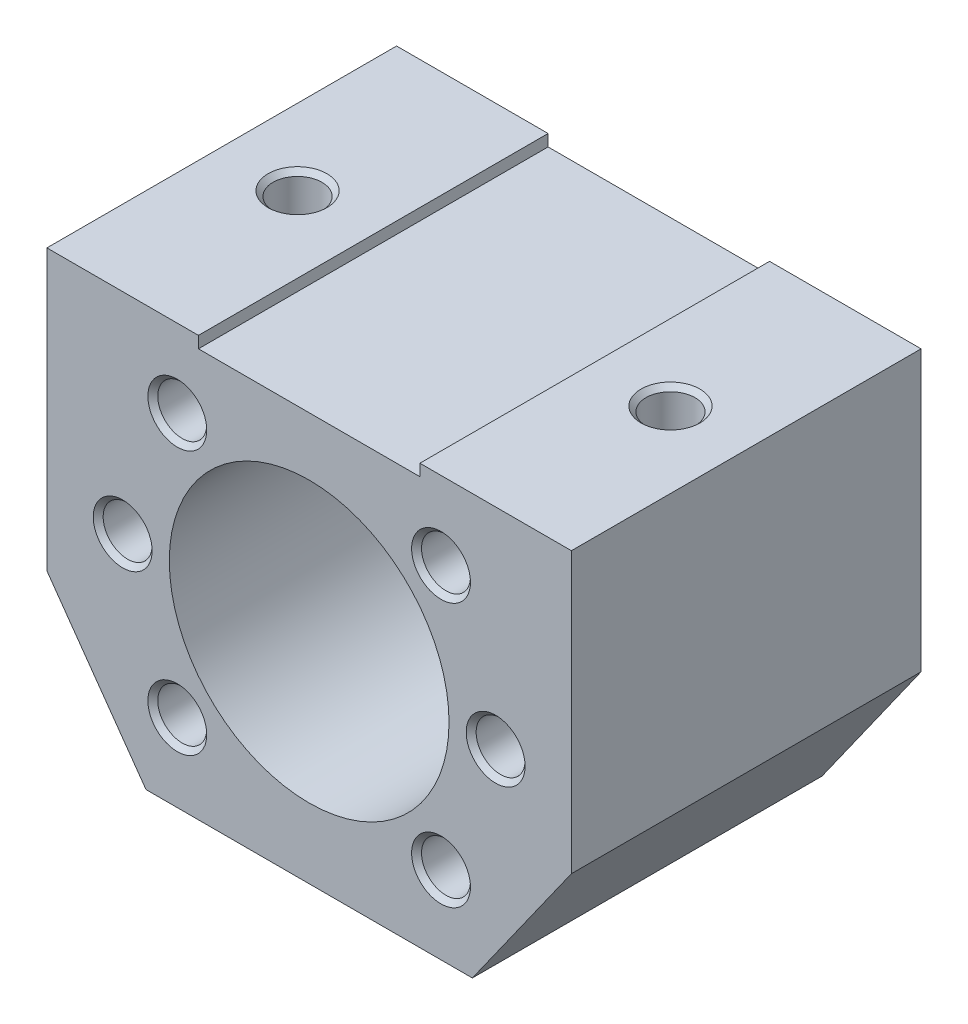
SolidWorks part; units mm, degrees
ref_plane "Спереди" through (0, 0, 0) normal (0, 0, 1) x (1, 0, 0)
ref_plane "Сверху" through (0, 0, 0) normal (0, 1, 0) x (1, 0, 0)
ref_plane "Справа" through (0, 0, 0) normal (1, 0, 0) x (0, 0, -1)
sketch "Эскиз1" plane through (0, 0, 0) normal (0, 0, 1) x (1, 0, 0)
  line L0 (-22.5, 18) -> (0, 18)
  line L1 (22.5, 18) -> (22.5, -6)
  line L2 (22.5, -6) -> (14, -18)
  line L3 (14, -18) -> (-14, -18)
  line L4 (-14, -18) -> (-22.5, -6)
  line L5 (-22.5, -6) -> (-22.5, 18)
  line L6 (0, 18) -> (22.5, 18)
  line L7 (0, 18) -> (0, 0) construction
  line L8 (0, 0) -> (0, -18) construction
  circle A0 centre (0, 0) radius 12
  dimension "D6" = 24
  dimension "D1" = 28
  dimension "D2" = 12
  dimension "D4" = 45
  dimension "D5" = 36
extrude "База" add sketch "Эскиз1" against normal blind 30
sketch "Крепление гайки" plane through (0, 0, 0) normal (0, 0, 1) x (1, 0, 0)
  line L0 (0, 0) -> (0, 32.6919) construction
  circle A0 centre (0, 0) radius 16 construction
  dimension "D1" = 32
hole_wizard "Гайка М5" positions "Эскиз4" profile "Эскиз3" tap size "M5" standard "Iso" end condition through all
sketch "Эскиз4" plane through (0, 0, 0) normal (0, 0, 1) x (1, 0, 0)
  circle A0 centre (0, 0) radius 16 construction
  point P0 (-16, 0)
cosmetic thread "Отверстие резьбы1"
sketch "Эскиз3" plane through (-16, 0, 0) normal (1, 0, 0) x (0, -1, 0)
  line L0 (0, 0) -> (0, 30)
  line L1 (0, 30) -> (2.1, 30)
  line L2 (2.1, 30) -> (2.1, 0.425)
  line L3 (2.1, 0.425) -> (2.525, 0)
  line L5 (2.525, 0) -> (0, 0)
  line L6 (-2.1, 0.425) -> (-2.525, 0) construction
  line L11 (0, -6.35) -> (0, 107.95) construction
  dimension "Диаметр проходного сверла" = 4.2
  dimension "Глубина проходного сверла" = 30
  dimension "Диаметр передней зенковки" = 5.05
  dimension "Угол передней зенковки" = 90
pattern_circular "Массив крепления" count 8 over 360 about axis through (0, 0, 0) along (0, 0, 1) skipping 2, 6 of "Гайка М5"
sketch "Эскиз27" plane through (0, 18, 0) normal (0, 1, 0) x (1, 0, 0)
  line L0 (22.5, 30) -> (-22.5, 30) construction
  line L1 (-9.5, 30) -> (9.5, 30)
  line L2 (-9.5, 30) -> (-9.5, 0)
  line L3 (-9.5, 0) -> (9.5, 0)
  line L4 (9.5, 30) -> (9.5, 0)
  line L5 (22.5, 0) -> (-22.5, 0) construction
  point P8 (0, 30)
  point P9 (0, 30)
  dimension "D1" = 19
extrude "Вырез Верх" cut sketch "Эскиз27" against normal blind 1
hole_wizard "Крепление держателя" positions "Эскиз7" profile "Эскиз6" tap size "M5" standard "Iso"
sketch "Эскиз7" plane through (0, 18, 0) normal (0, 1, 0) x (1, 0, 0)
  line L4 (-16, 15) -> (-16, 0) construction
  line L5 (-16, 0) -> (16, 0) construction
  line L18 (-16, 15) -> (-22.5, 15) construction
  line L22 (-16, 15) -> (-9.5, 15) construction
  line L26 (16, 15) -> (9.5, 15) construction
  line L30 (16, 15) -> (22.5, 15) construction
  line L34 (-22.5, 30) -> (-22.5, 0) construction
  line L36 (9.5, 0) -> (9.5, 30) construction
  line L37 (22.5, 30) -> (22.5, 0) construction
  line L38 (-16, 15) -> (-16, 30) construction
  line L39 (-9.5, 30) -> (-22.5, 30) construction
  point P4 (16, 15)
  point P6 (-16, 15)
sketch "Эскиз6" plane through (16, 18, -15) normal (1, 0, 0) x (0, 0, 1)
  line L0 (0, 0) -> (0, 16.2618)
  line L1 (0, 16.2618) -> (2.1, 15)
  line L2 (2.1, 15) -> (2.1, 0.425)
  line L3 (2.1, 0.425) -> (2.525, 0)
  line L5 (2.525, 0) -> (0, 0)
  line L6 (-2.1, 0.425) -> (-2.525, 0) construction
  line L10 (0, 16.2618) -> (-2.1, 15) construction
  line L11 (0, -6.35) -> (0, 107.95) construction
  dimension "Диаметр сверла" = 4.2
  dimension "Глубина сверла" = 15
  dimension "Диаметр передней зенковки" = 5.05
  dimension "Угол передней зенковки" = 90
  dimension "Угол заточки сверла" = 118
cosmetic thread "Отверстие резьбы2"
cosmetic thread "Отверстие резьбы3"
